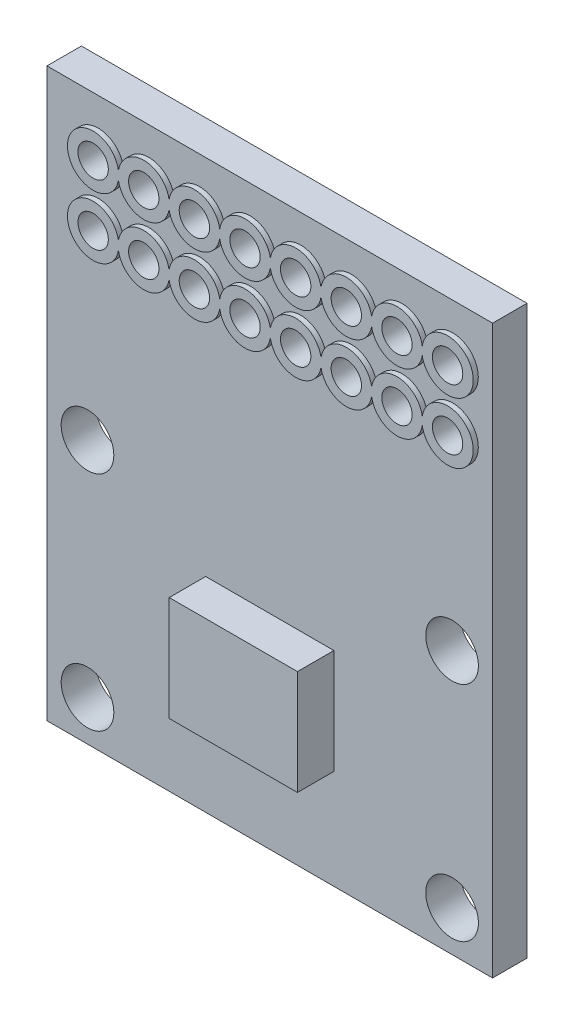
SolidWorks part; units mm, degrees
material "Epoxy, renforcé"
ref_plane "Plan de face" through (0, 0, 0) normal (0, 0, 1) x (1, 0, 0)
ref_plane "Plan de dessus" through (0, 0, 0) normal (0, 1, 0) x (1, 0, 0)
ref_plane "Plan de droite" through (0, 0, 0) normal (1, 0, 0) x (0, 0, -1)
sketch "Esquisse1" plane through (0, 0, 0) normal (0, 0, 1) x (1, 0, 0)
  line L0 (0, 1) -> (0, -14) construction
  line L1 (-11, -14) -> (11, -14)
  line L2 (-11, -14) -> (-11, 14)
  line L3 (-11, 14) -> (11, 14)
  line L4 (11, -14) -> (11, 14)
  line L5 (-11, -14) -> (11, 14) construction
  line L6 (-11, 14) -> (11, -14) construction
  line L7 (-11, 1) -> (11, 1) construction
  line L8 (0, -12) -> (9, -12) construction
  line L9 (0, -12) -> (-9, -12) construction
  line L10 (-9, -12) -> (-9, -1) construction
  line L11 (9, -12) -> (9, -1) construction
  line L12 (0, -6.5) -> (11, -6.5) construction
  circle A0 centre (-9, -1) radius 1.3
  circle A1 centre (9, -1) radius 1.3
  circle A2 centre (9, -12) radius 1.3
  circle A3 centre (-9, -12) radius 1.3
  point P0 (0, 0)
  point P22 (9, -6.5)
  dimension "D5" = 2.6
  dimension "D1" = 22
  dimension "D2" = 28
  dimension "D3" = 9
  dimension "D4" = 11
  dimension "D6" = 15
extrude "Boss.-Extru.1" add sketch "Esquisse1" along normal blind 1.7
sketch "Esquisse2" plane through (0, 0, 1.7) normal (0, 0, 1) x (1, 0, 0)
  line L0 (-9, -12) -> (9, -1) construction
  line L2 (-3.165, -9.085) -> (3.165, -9.085)
  line L3 (-3.165, -9.085) -> (-3.165, -3.915)
  line L4 (-3.165, -3.915) -> (3.165, -3.915)
  line L5 (3.165, -9.085) -> (3.165, -3.915)
  line L6 (-3.165, -9.085) -> (3.165, -3.915) construction
  line L7 (-3.165, -3.915) -> (3.165, -9.085) construction
  point P4 (0, -6.5)
  dimension "D1" = 6.33
  dimension "D2" = 5.17
extrude "Boss.-Extru.2" add sketch "Esquisse2" along normal blind 1.8
sketch "Esquisse3" plane through (0, 0, 1.7) normal (0, 0, 1) x (1, 0, 0)
  line L0 (-11, 11.3366) -> (11, 11.3366) construction
  line L1 (-11, 14) -> (-11, -14) construction
  line L2 (11, -14) -> (11, 14) construction
  circle A0 centre (-8.4718, 11.3366) radius 0.75
  dimension "D1" = 1.5
extrude "Enlèv. mat.-Extru.1" cut sketch "Esquisse3" against normal through all
pattern_linear "Répétition linéaire1" count 8 spacing 2.5 along (1, 0, 0) count 2 spacing 3 along (0, -1, 0) of "Enlèv. mat.-Extru.1"
sketch "Esquisse4" plane through (0, 0, 1.7) normal (0, 0, 1) x (1, 0, 0)
  circle A0 centre (-8.4718, 11.3366) radius 1.267
  circle A1 centre (-8.4718, 11.3366) radius 0.75
extrude "Boss.-Extru.3" add sketch "Esquisse4" along normal blind 0.25 and the other way blind 1.9
pattern_linear "Répétition linéaire2" count 8 spacing 2.5 along (1, 0, 0) count 2 spacing 3 along (0, -1, 0) of "Boss.-Extru.3"
